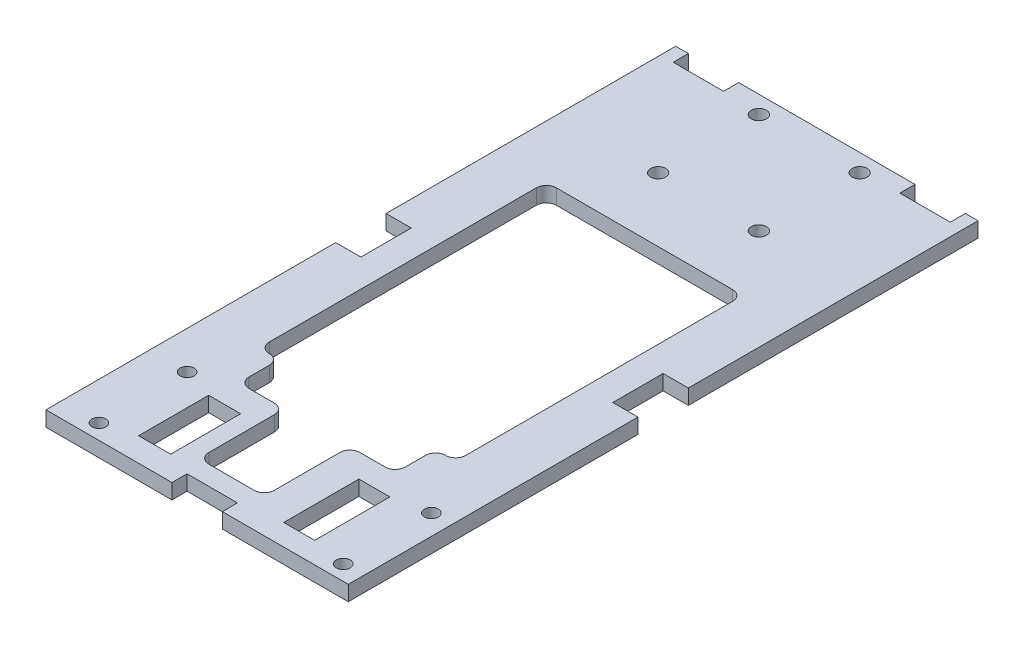
SolidWorks part; units mm, degrees
material "Acrílico (Impacto medio-alto)"
ref_plane "Alzado" through (0, 0, 0) normal (0, 0, 1) x (1, 0, 0)
ref_plane "Planta" through (0, 0, 0) normal (0, 1, 0) x (1, 0, 0)
ref_plane "Vista lateral" through (0, 0, 0) normal (1, 0, 0) x (0, 0, -1)
sketch "Croquis1" plane through (0, 0, 0) normal (0, 1, 0) x (1, 0, 0)
  line L0 (35, 3) -> (35, 0) construction
  line L1 (0, 0) -> (25, 0)
  line L2 (0, 0) -> (0, 57.5)
  line L3 (0, 125) -> (2.5, 125)
  line L4 (60, 0) -> (60, 57.5)
  line L5 (25, 3) -> (25, 0) construction
  line L6 (25, 3) -> (35, 3) construction
  line L7 (55, 67.5) -> (60, 67.5)
  line L9 (55, 67.5) -> (55, 57.5) construction
  line L12 (5, 67.5) -> (5, 57.5) construction
  line L13 (13.6428, 4.7345) -> (20, 4.7345)
  line L14 (13.6428, 4.7345) -> (13.6428, 18.6451)
  line L15 (13.6428, 18.6451) -> (20, 18.6451)
  line L16 (20, 4.7345) -> (20, 18.6451)
  line L17 (13.6428, 4.7345) -> (20, 18.6451) construction
  line L18 (13.6428, 18.6451) -> (20, 4.7345) construction
  line L19 (49.1085, 4.222) -> (42.9586, 4.222)
  line L20 (49.1085, 4.222) -> (49.1085, 19.1576)
  line L21 (49.1085, 19.1576) -> (42.9586, 19.1576)
  line L22 (42.9586, 4.222) -> (42.9586, 19.1576)
  line L23 (49.1085, 4.222) -> (42.9586, 19.1576) construction
  line L24 (49.1085, 19.1576) -> (42.9586, 4.222) construction
  line L27 (57.5, 122) -> (57.5, 125) construction
  line L28 (47.5, 122) -> (47.5, 125) construction
  line L29 (57.5, 122) -> (47.5, 122) construction
  line L30 (2.5, 122) -> (12.5, 122) construction
  line L31 (2.5, 125) -> (2.5, 122) construction
  line L32 (12.5, 125) -> (12.5, 122) construction
  line L33 (35, 3) -> (35, 0)
  line L34 (25, 3) -> (25, 0)
  line L35 (25, 3) -> (35, 3)
  line L38 (55, 67.5) -> (55, 57.5)
  line L41 (5, 67.5) -> (5, 57.5)
  line L44 (57.5, 122) -> (57.5, 125)
  line L45 (47.5, 122) -> (47.5, 125)
  line L46 (57.5, 122) -> (47.5, 122)
  line L47 (2.5, 122) -> (12.5, 122)
  line L48 (2.5, 125) -> (2.5, 122)
  line L49 (12.5, 125) -> (12.5, 122)
  line L50 (55, 57.5) -> (60, 57.5)
  line L51 (5, 67.5) -> (0, 67.5)
  line L52 (5, 57.5) -> (0, 57.5)
  line L53 (57.5, 125) -> (60, 125)
  line L54 (12.5, 125) -> (47.5, 125)
  line L55 (60, 67.5) -> (60, 125)
  line L56 (0, 67.5) -> (0, 125)
  line L57 (35, 0) -> (60, 0)
  line L75 (10.5, 33.818) -> (10.5, 86.818)
  line L76 (14.5, 29.818) -> (14.5, 25.818)
  line L77 (12.5, 88.818) -> (47.5, 88.818)
  line L78 (16.5, 23.818) -> (21.5, 23.818)
  line L79 (49.5, 86.818) -> (49.5, 33.818)
  line L80 (23.5, 21.818) -> (23.5, 8.818)
  line L82 (30, 31.818) -> (30, 88.818) construction
  line L83 (45.5, 29.818) -> (45.5, 25.818)
  line L84 (43.5, 23.818) -> (38.5, 23.818)
  line L85 (36.5, 21.818) -> (36.5, 8.818)
  line L86 (25.5, 6.818) -> (34.5, 6.818)
  circle A0 centre (20, 101.5) radius 1.5 construction
  circle A1 centre (20, 121.5) radius 1.5 construction
  circle A2 centre (40, 121.5) radius 1.5 construction
  circle A3 centre (40, 101.5) radius 1.5 construction
  circle A4 centre (20, 101.5) radius 1.5
  circle A5 centre (20, 121.5) radius 1.5
  circle A6 centre (40, 121.5) radius 1.5
  circle A7 centre (40, 101.5) radius 1.5
  arc A8 (45.5, 25.818) -> (43.5, 23.818) centre (43.5, 25.818) cw
  arc A9 (38.5, 23.818) -> (36.5, 21.818) centre (38.5, 21.818) ccw
  arc A10 (36.5, 8.818) -> (34.5, 6.818) centre (34.5, 8.818) cw
  arc A11 (23.5, 8.818) -> (25.5, 6.818) centre (25.5, 8.818) ccw
  arc A12 (21.5, 23.818) -> (23.5, 21.818) centre (21.5, 21.818) cw
  arc A13 (14.5, 25.818) -> (16.5, 23.818) centre (16.5, 25.818) ccw
  arc A14 (14.5, 29.818) -> (12.5, 31.818) centre (12.5, 29.818) ccw
  arc A15 (49.5, 33.818) -> (47.5, 31.818) centre (47.5, 33.818) cw
  arc A16 (45.5, 29.818) -> (47.5, 31.818) centre (47.5, 29.818) cw
  arc A17 (10.5, 33.818) -> (12.5, 31.818) centre (12.5, 33.818) ccw
  arc A18 (47.5, 88.818) -> (49.5, 86.818) centre (47.5, 86.818) cw
  arc A19 (10.5, 86.818) -> (12.5, 88.818) centre (12.5, 86.818) cw
  circle A36 centre (7.5, 3) radius 1.375
  circle A37 centre (7.5, 20.5) radius 1.375
  circle A38 centre (56, 20.5) radius 1.375
  circle A39 centre (56, 3) radius 1.375
  point P25 (16.8214, 11.6898)
  point P30 (46.0335, 11.6898)
  point P60 (45.5, 23.818)
  point P66 (36.5, 23.818)
  point P71 (36.5, 6.818)
  point P74 (23.5, 6.818)
  point P77 (23.5, 23.818)
  point P80 (14.5, 23.818)
  dimension "D9" = 2
  dimension "D10" = 2
  dimension "D11" = 2.75
  dimension "D1" = 60
  dimension "D2" = 125
  dimension "D3" = 6.3572
  dimension "D4" = 13.9105
  dimension "D5" = 10.5
  dimension "D6" = 10.5
  dimension "D7" = 9
  dimension "D8" = 17
extrude "Saliente-Extruir1" add sketch "Croquis1" along normal blind 3
